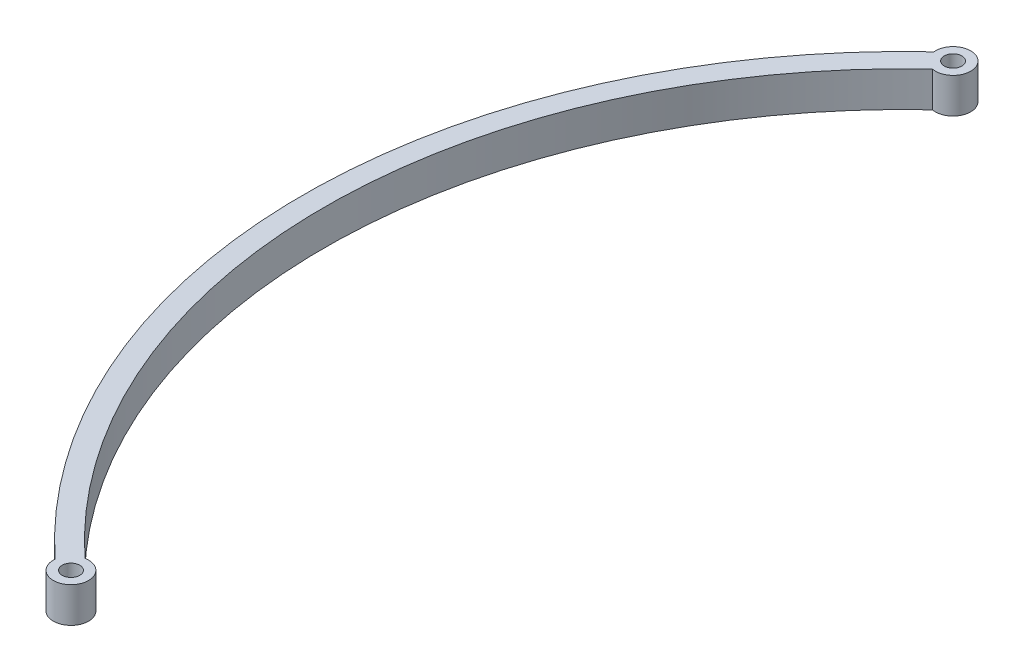
SolidWorks part; units mm, degrees
ref_plane "Plan de face" through (0, 0, 0) normal (0, 0, 1) x (1, 0, 0)
ref_plane "Plan de dessus" through (0, 0, 0) normal (0, 1, 0) x (1, 0, 0)
ref_plane "Plan de droite" through (0, 0, 0) normal (1, 0, 0) x (0, 0, -1)
sketch "Esquisse1" plane through (0, 0, 0) normal (0, 1, 0) x (1, 0, 0)
  arc A0 (-0.9437, 213.6989) -> (-4.978, 218.1407) centre (0, 218.6091) ccw
  arc A1 (-4.978, -30.9226) -> (-0.9437, -26.4808) centre (0, -31.3909) ccw
  arc A3 (-4.978, 218.1407) -> (-4.978, -30.9226) centre (110.8308, 93.6091) ccw
  arc A4 (-0.9437, 213.6989) -> (-0.9437, -26.4808) centre (110.8308, 93.6091) ccw
  point P5 (110.8308, 93.6091)
  point P10 (110.8308, 260.6674)
  dimension "D1" = 10
  dimension "D2" = 10
  dimension "D3" = 250
extrude "Boss.-Extru.1" add sketch "Esquisse1" along normal blind 10
sketch "Esquisse2" plane through (0, 10, 0) normal (0, 1, 0) x (1, 0, 0)
  circle A0 centre (0, 218.6091) radius 2.5
  circle A1 centre (0, -31.3909) radius 2.5
  dimension "D1" = 5
  dimension "D2" = 5
extrude "Enlèv. mat.-Extru.1" cut sketch "Esquisse2" against normal blind 10
